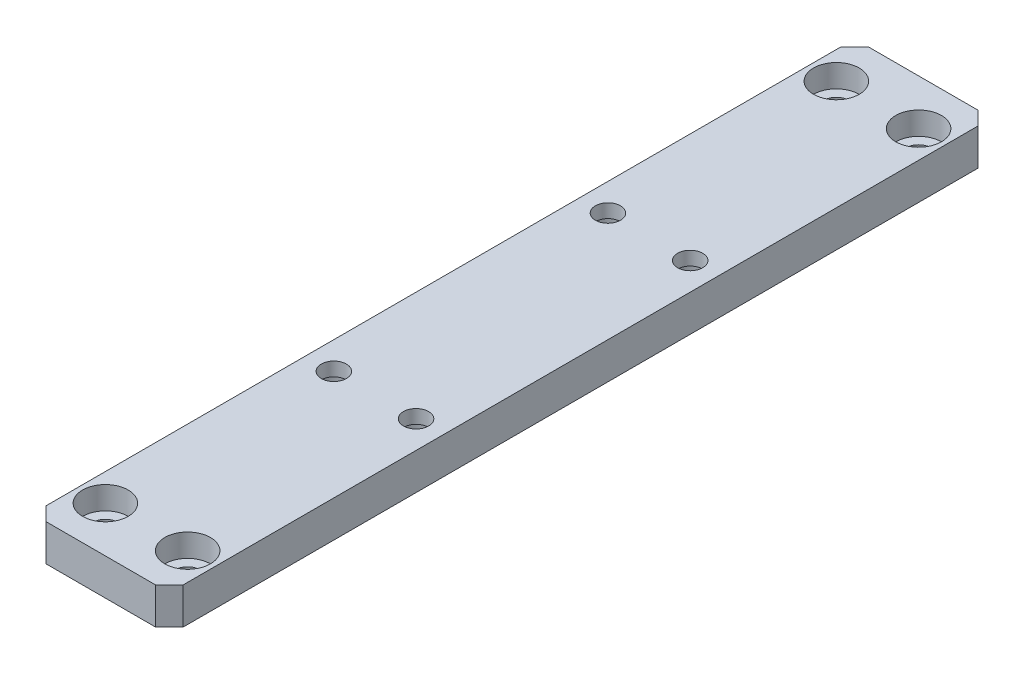
SolidWorks part; units mm, degrees
ref_plane "Front" through (0, 0, 0) normal (0, 0, 1) x (1, 0, 0)
ref_plane "Top" through (0, 0, 0) normal (0, 1, 0) x (1, 0, 0)
ref_plane "Right" through (0, 0, 0) normal (1, 0, 0) x (0, 0, -1)
sketch "Sketch1" plane through (0, 0, 0) normal (0, 1, 0) x (1, 0, 0)
  line L0 (-34.5828, 0) -> (109.3019, 0) construction
  line L1 (0, 90) -> (30, 90)
  line L2 (0, 90) -> (0, -90)
  line L3 (0, -90) -> (30, -90)
  line L4 (30, 90) -> (30, -90)
  dimension "D2" = 180
  dimension "D3" = 30
extrude "Boss-Extrude1" add sketch "Sketch1" along normal blind 8
chamfer "Chamfer1" distance 3 angle 45 4 edges at (30, 4, -90) (30, 4, 90) (0, 4, 90) (0, 4, -90)
hole_wizard "CBORE for M5 Socket Head Cap Screw1" positions "Sketch2" profile "Sketch3" counterbore size "M5" standard "JIS" end condition through all
sketch "Sketch2" plane through (0, 8, 0) normal (0, 1, 0) x (-1, 0, 0)
  line L0 (19.7184, 0) -> (-83.1709, 0) construction
  line L2 (-30, 87) -> (-30, -87) construction
  point P0 (-6, -80)
  point P1 (-6, 80)
  point P3 (-24, 80)
  point P5 (-24, -80)
  dimension "D1" = 160
  dimension "D2" = 6
  dimension "D3" = 18
sketch "Sketch3" plane through (6, 8, -80) normal (1, 0, 0) x (0, 0, 1)
  line L0 (0, 0) -> (0, 8)
  line L1 (0, 8) -> (2.75, 8)
  line L3 (2.75, 8) -> (2.75, 5)
  line L4 (2.75, 5) -> (5, 5)
  line L5 (5, 5) -> (5, 0)
  line L7 (5, 0) -> (0, 0)
  line L11 (0, -6.35) -> (0, 107.95) construction
  dimension "通し穴の直径" = 5.5
  dimension "通し穴の深さ" = 8
  dimension "座ぐり穴の直径" = 10
  dimension "座ぐり穴の深さ" = 5
hole_wizard "CBORE for M5 Socket Head Cap Screw2" positions "Sketch4" profile "Sketch5" counterbore size "M5" standard "JIS" end condition through all
sketch "Sketch4" plane through (0, 0, 0) normal (0, -1, 0) x (1, 0, 0)
  line L0 (-15.0847, 0) -> (75.3153, 0) construction
  line L2 (0, -87) -> (0, 87) construction
  line L3 (30, 87) -> (30, -87) construction
  point P0 (6, 30)
  point P1 (6, -30)
  point P3 (24, -30)
  point P5 (24, 30)
  dimension "D1" = 60
  dimension "D2" = 18
  dimension "D3" = 6
  dimension "D4" = 6
sketch "Sketch5" plane through (6, 0, 30) normal (1, 0, 0) x (0, 0, -1)
  line L0 (0, 0) -> (0, 8)
  line L1 (0, 8) -> (2.75, 8)
  line L3 (2.75, 8) -> (2.75, 5)
  line L4 (2.75, 5) -> (5, 5)
  line L5 (5, 5) -> (5, 0)
  line L7 (5, 0) -> (0, 0)
  line L11 (0, -6.35) -> (0, 107.95) construction
  dimension "通し穴の直径" = 5.5
  dimension "通し穴の深さ" = 8
  dimension "座ぐり穴の直径" = 10
  dimension "座ぐり穴の深さ" = 5
